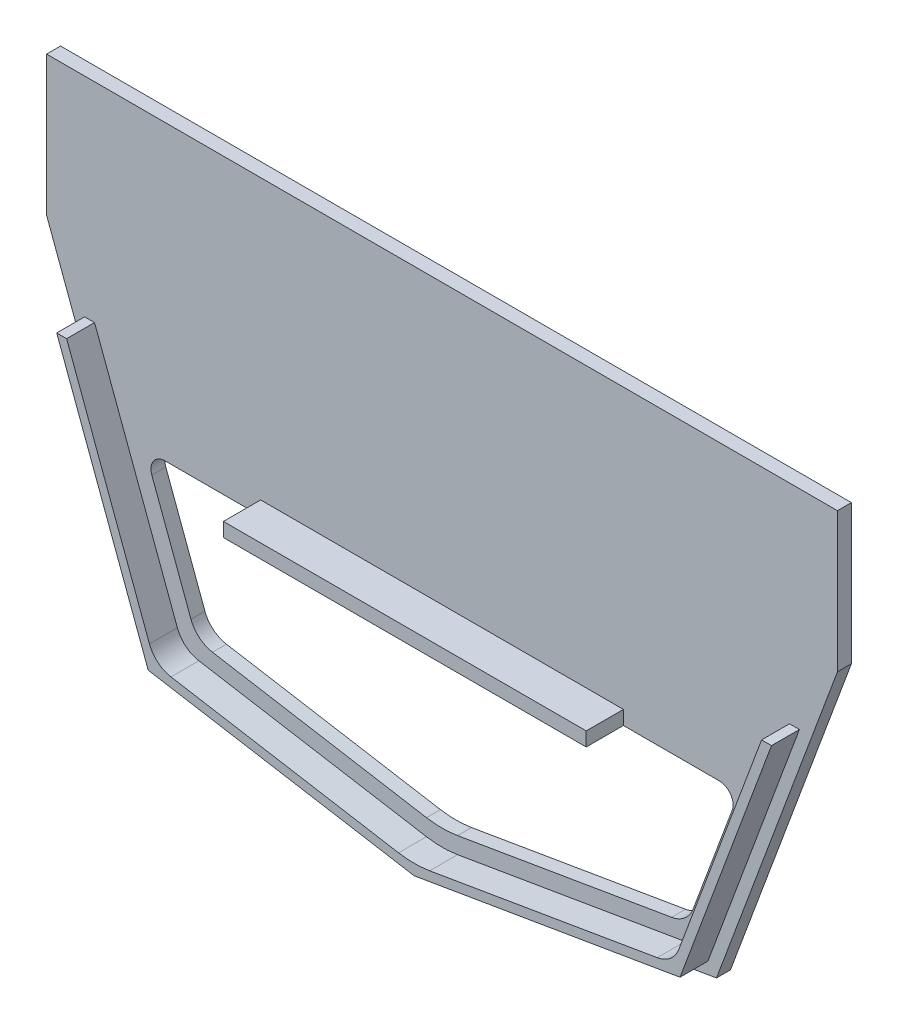
SolidWorks part; units mm, degrees
ref_plane "Front Plane" through (0, 0, 0) normal (0, 0, 1) x (1, 0, 0)
ref_plane "Top Plane" through (0, 0, 0) normal (0, 1, 0) x (1, 0, 0)
ref_plane "Right Plane" through (0, 0, 0) normal (1, 0, 0) x (0, 0, -1)
sketch "Sketch2" plane through (0, 0, 0) normal (0, 0, 1) x (1, 0, 0)
  line L1 (63.8855, -33) -> (52.7622, -62.9425)
  line L2 (52.7622, -62.9425) -> (0, -71.8859)
  line L3 (-63.8855, -33) -> (63.8855, -33)
  line L4 (0, -71.8859) -> (-52.7622, -62.9425)
  line L5 (-52.7622, -62.9425) -> (-63.8855, -33)
  line L14 (85, 0) -> (85, 30)
  line L15 (85, 30) -> (-85, 30)
  line L16 (-85, 30) -> (-85, 0)
  line L17 (-85, 0) -> (-58.9956, -70)
  line L18 (-58.9956, -70) -> (0, -80)
  line L19 (0, -80) -> (58.9956, -70)
  line L20 (58.9956, -70) -> (85, 0)
extrude "Boss-Extrude1" add sketch "Sketch2" along normal blind 3
sketch "Sketch3" plane through (0, 0, 3) normal (0, 0, 1) x (1, 0, 0)
  line L0 (-74.6918, -14.8259) -> (-55.6821, -65.9975)
  line L3 (-55.6821, -65.9975) -> (0, -75.4358)
  line L20 (-76.8254, -14.8259) -> (-57.1548, -67.7764)
  line L21 (-57.1548, -67.7764) -> (0, -77.4643)
  line L22 (0, -77.4643) -> (57.1548, -67.7764)
  line L23 (57.1548, -67.7764) -> (76.8254, -14.8259)
  line L25 (0, -75.4358) -> (55.6821, -65.9975)
  line L26 (55.6821, -65.9975) -> (74.6918, -14.8259)
  line L27 (-76.8254, -14.8259) -> (-74.6918, -14.8259)
  line L28 (74.6918, -14.8259) -> (76.8254, -14.8259)
  line L29 (55.6821, -65.9975) -> (74.9506, -14.1294) construction
  line L30 (-74.9506, -14.1294) -> (-55.6821, -65.9975) construction
  dimension "D1" = 2
extrude "Boss-Extrude2" add sketch "Sketch3" along normal blind 6
fillet "Fillet1" radius 20 2 edges at (0, -75.4358, 6) (0, -71.8859, 1.5)
fillet "Fillet2" radius 6 4 edges at (-52.7622, -62.9425, 1.5) (-55.6821, -65.9975, 6) (55.6821, -65.9975, 6) (52.7622, -62.9425, 1.5)
fillet "Fillet4" radius 3 2 edges at (-63.8855, -33, 1.5) (63.8855, -33, 1.5)
sketch "Sketch4" plane through (0, 0, 3) normal (0, 0, 1) x (1, 0, 0)
  line L0 (59.5707, -33) -> (-59.5707, -33) construction
  line L1 (-38.9956, -33) -> (38.9956, -33)
  line L2 (-38.9956, -33) -> (-38.9956, -30)
  line L3 (-38.9956, -30) -> (38.9956, -30)
  line L4 (38.9956, -33) -> (38.9956, -30)
  dimension "D1" = 3
  dimension "D2" = 20
  dimension "D3" = 20
extrude "Boss-Extrude3" add sketch "Sketch4" along normal blind 8
